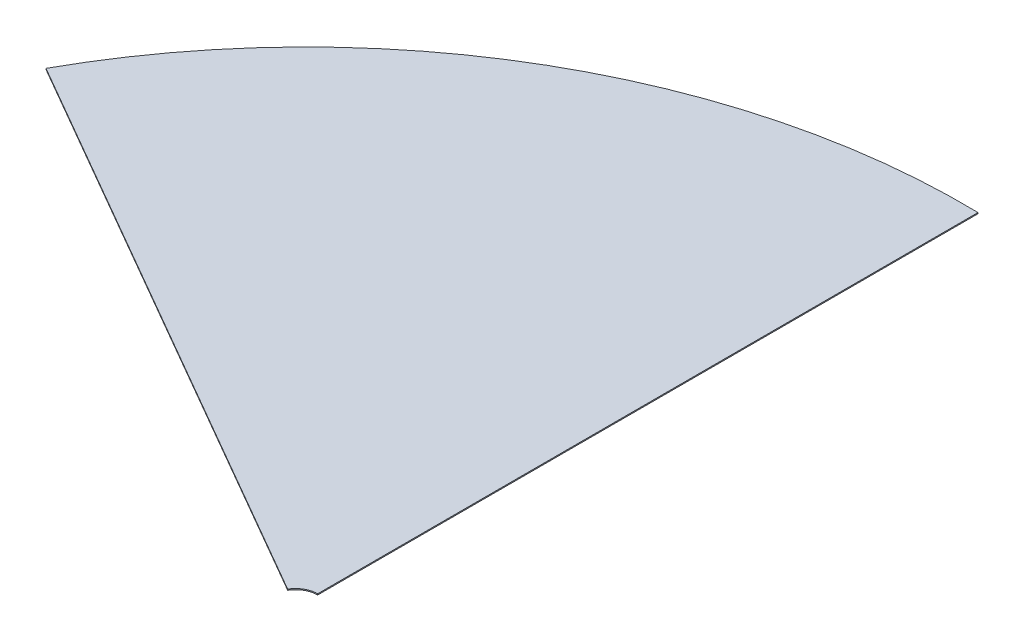
SolidWorks part; units mm, degrees
ref_plane "Front Plane" through (0, 0, 0) normal (0, 0, 1) x (1, 0, 0)
ref_plane "Top Plane" through (0, 0, 0) normal (0, 1, 0) x (1, 0, 0)
ref_plane "Right Plane" through (0, 0, 0) normal (1, 0, 0) x (0, 0, -1)
sketch "Sketch1" plane through (0, 0, 0) normal (0, 1, 0) x (1, 0, 0)
  line L0 (0, 10) -> (0, 310.47)
  line L1 (-8.6603, 5) -> (-268.8749, 155.235)
  arc A0 (0, 10) -> (-8.6603, 5) centre (0, 0) ccw
  arc A1 (-268.8749, 155.235) -> (0, 310.47) centre (-6.3727, 11.0378) cw
  dimension "D2" = 60
  dimension "D4" = 299.5
  dimension "D1" = 10
  dimension "D3" = 300.47
extrude "Boss-Extrude1" add sketch "Sketch1" along normal blind 0.5
